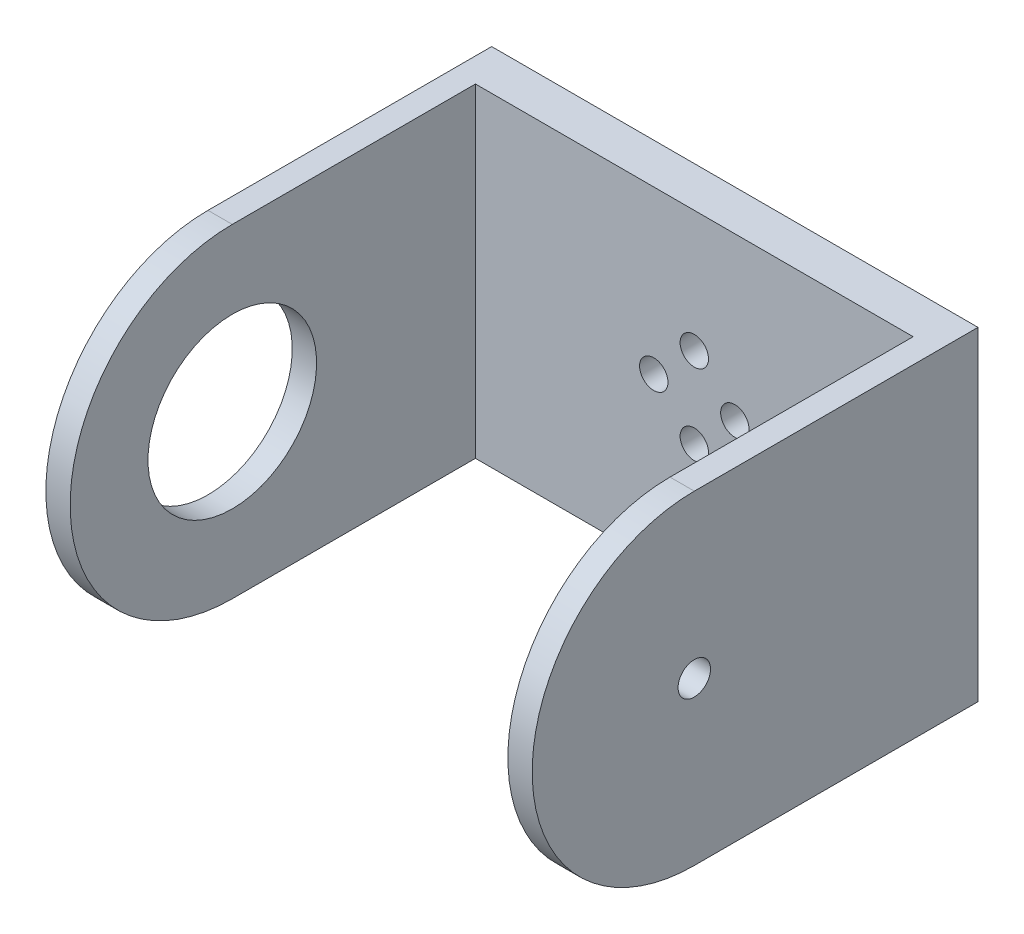
SolidWorks part; units mm, degrees
material "ABS"
ref_plane "Front Plane" through (0, 0, 0) normal (0, 0, 1) x (1, 0, 0)
ref_plane "Top Plane" through (0, 0, 0) normal (0, 1, 0) x (1, 0, 0)
ref_plane "Right Plane" through (0, 0, 0) normal (1, 0, 0) x (0, 0, -1)
sketch "Sketch1" plane through (0, 0, 0) normal (0, 0, 1) x (1, 0, 0)
  line L1 (-30, 20) -> (30, 20)
  line L2 (-30, 20) -> (-30, -20)
  line L3 (-30, -20) -> (30, -20)
  line L4 (30, 20) -> (30, -20)
  line L5 (-30, 20) -> (30, -20) construction
  line L6 (-30, -20) -> (30, 20) construction
  point P0 (0, 0)
  dimension "D1" = 60
  dimension "D2" = 40
extrude "Boss-Extrude1" add sketch "Sketch1" along normal blind 5
sketch "Sketch3" plane through (0, 0, 5) normal (0, 0, 1) x (1, 0, 0)
  line L0 (-30, 20) -> (-30, -20)
  line L1 (-30, -20) -> (-27, -20)
  line L2 (-30, -20) -> (30, -20) construction
  line L3 (-27, -20) -> (-27, 20)
  line L4 (30, 20) -> (-30, 20) construction
  line L5 (-27, 20) -> (-30, 20)
  line L6 (30, -20) -> (27, -20)
  line L7 (27, -20) -> (27, 20)
  line L8 (27, 20) -> (30, 20)
  line L9 (30, 20) -> (30, -20)
  dimension "D1" = 3
  dimension "D2" = 3
extrude "Boss-Extrude2" add sketch "Sketch3" along normal blind 30
sketch "Sketch9" plane through (30, 0, 0) normal (1, 0, 0) x (0, 0, -1)
  line L0 (-35, 20) -> (-35, -20)
  arc A0 (-35, 20) -> (-35, -20) centre (-35, 0) ccw
  dimension "D1" = 20
extrude "Boss-Extrude3" add sketch "Sketch9" against normal blind 3
sketch "Sketch10" plane through (-30, 0, 0) normal (-1, 0, 0) x (0, 0, 1)
  line L0 (35, 20) -> (35, -20) construction
  line L1 (35, 20) -> (35, -20)
  arc A0 (35, 20) -> (35, -20) centre (35, 0) cw
  arc A1 (35, -20) -> (35, 20) centre (35, 0) ccw construction
  dimension "D1" = 20
extrude "Boss-Extrude4" add sketch "Sketch10" against normal blind 3
sketch "Sketch8" plane through (0, 0, 0) normal (0, 0, -1) x (-1, 0, 0)
  line L0 (-30, 20) -> (30, 20) construction
  line L1 (0, -2.3042) -> (0, 2.2571) construction
  line L2 (-2.5626, 0) -> (2.6505, 0) construction
  line L3 (-30, -20) -> (-30, 20) construction
  circle A2 centre (-5, 0) radius 1.75
  circle A5 centre (0, 5) radius 1.75
  circle A6 centre (0, -5) radius 1.75
  circle A7 centre (5, 0) radius 1.75
  dimension "D1" = 3.5
  dimension "D3" = 5
  dimension "D2" = 3.5
  dimension "D4" = 20
  dimension "D5" = 5
  dimension "D6" = 30
extrude "Cut-Extrude1" cut sketch "Sketch8" against normal through all
sketch "Sketch11" plane through (-30, 0, 0) normal (-1, 0, 0) x (0, 0, 1)
  circle A0 centre (35, 0) radius 10.4
  dimension "D1" = 20.8
extrude "Cut-Extrude2" cut sketch "Sketch11" against normal blind 3 and the other way through all
sketch "Sketch13" plane through (30, 0, 0) normal (1, 0, 0) x (0, 0, -1)
  circle A0 centre (-35, 0) radius 2
  dimension "D1" = 4
extrude "Cut-Extrude3" cut sketch "Sketch13" against normal blind 10
